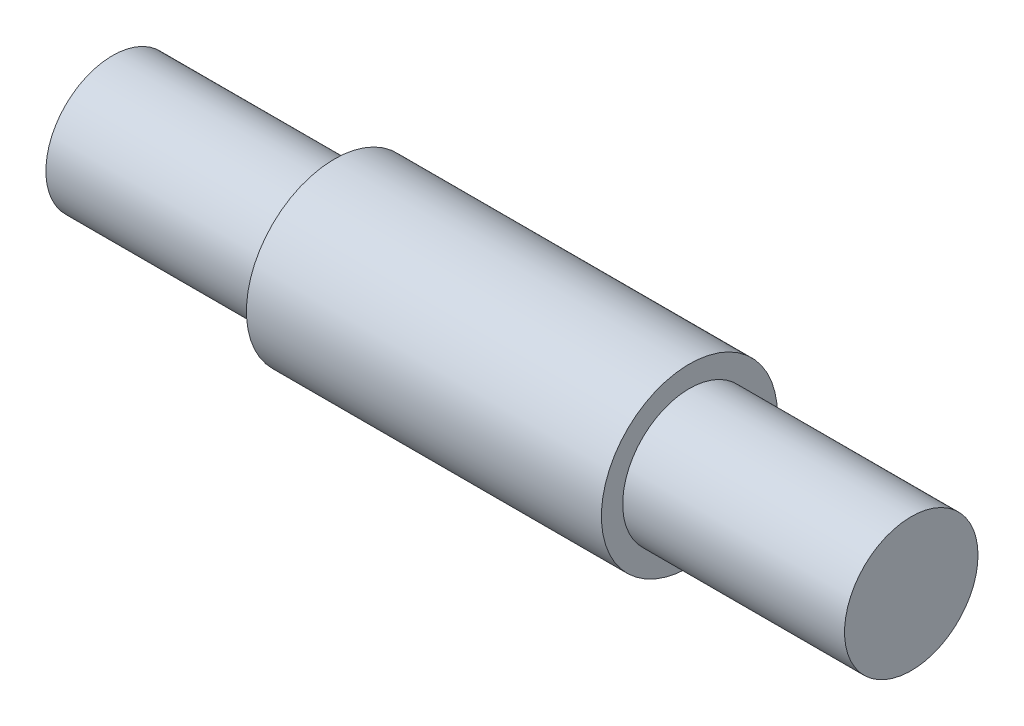
SolidWorks part; units mm, degrees
ref_plane "Front Plane" through (0, 0, 0) normal (0, 0, 1) x (1, 0, 0)
ref_plane "Top Plane" through (0, 0, 0) normal (0, 1, 0) x (1, 0, 0)
ref_plane "Right Plane" through (0, 0, 0) normal (1, 0, 0) x (0, 0, -1)
sketch "Sketch1" plane through (0, 0, 0) normal (1, 0, 0) x (0, 0, -1)
  circle A0 centre (0, 0) radius 3.1496
  dimension "D1" = 6.2992
extrude "Boss-Extrude1" add sketch "Sketch1" along normal mid plane 28.575
sketch "Sketch3" plane through (14.2875, 0, 0) normal (1, 0, 0) x (0, 0, -1)
  circle A0 centre (0, 0) radius 3.1496
  circle A1 centre (0, 0) radius 2.3876
  dimension "D1" = 4.7752
extrude "Cut-Extrude2" cut sketch "Sketch3" against normal blind 7.9375
mirror "Mirror1" about plane through (0, 0, 0) normal (1, 0, 0) of "Cut-Extrude2"
